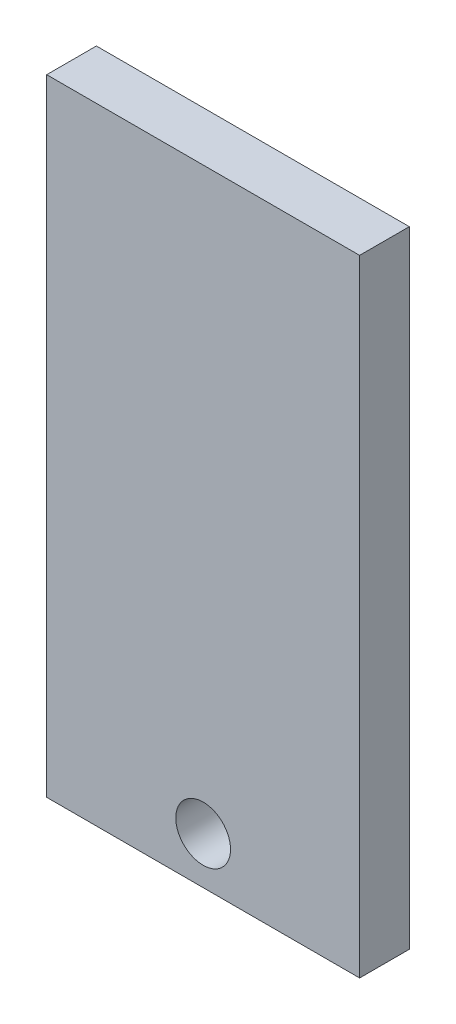
SolidWorks part; units mm, degrees
ref_plane "Front Plane" through (0, 0, 0) normal (0, 0, 1) x (1, 0, 0)
ref_plane "Top Plane" through (0, 0, 0) normal (0, 1, 0) x (1, 0, 0)
ref_plane "Right Plane" through (0, 0, 0) normal (1, 0, 0) x (0, 0, -1)
sketch "Sketch1" plane through (0, 0, 0) normal (0, 0, 1) x (1, 0, 0)
  line L1 (-20, 40) -> (20, 40)
  line L2 (-20, 40) -> (-20, -40)
  line L3 (-20, -40) -> (20, -40)
  line L4 (20, 40) -> (20, -40)
  line L5 (-20, 40) -> (20, -40) construction
  line L6 (-20, -40) -> (20, 40) construction
  point P0 (0, 0)
  dimension "D1" = 40
  dimension "D2" = 80
extrude "Boss-Extrude1" add sketch "Sketch1" along normal blind 6.35
sketch "Sketch2" plane through (0, 0, 6.35) normal (0, 0, 1) x (1, 0, 0)
  circle A0 centre (0, -34.0195) radius 3.5
extrude "Cut-Extrude1" cut sketch "Sketch2" against normal up to next
